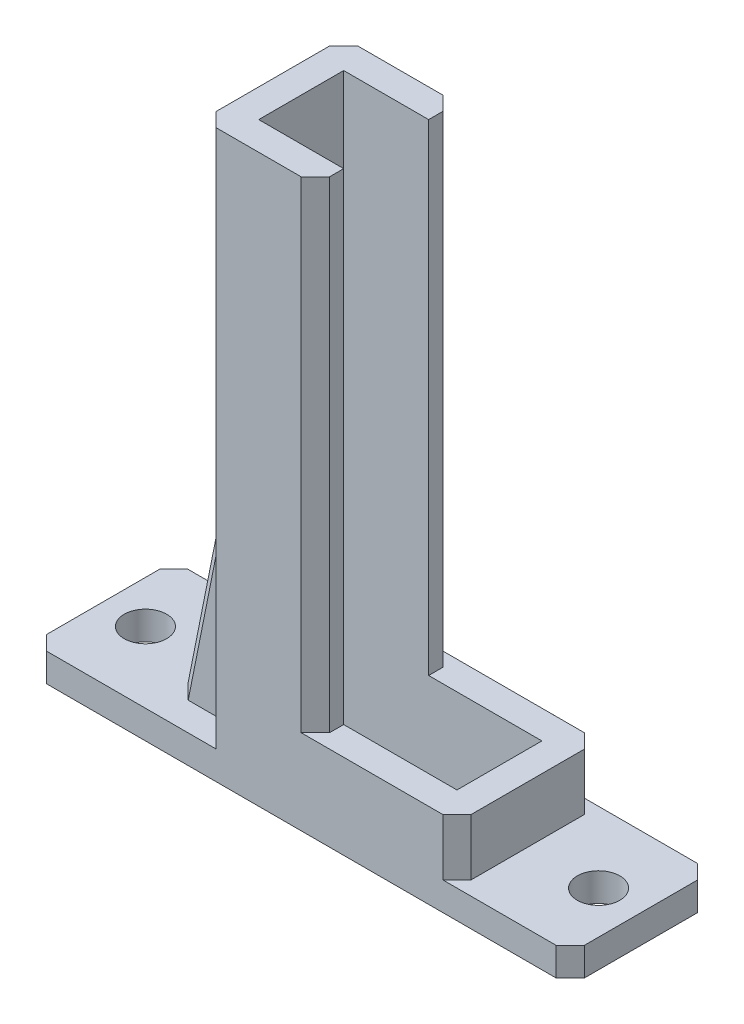
SolidWorks part; units mm, degrees
ref_plane "Front Plane" through (0, 0, 0) normal (0, 0, 1) x (1, 0, 0)
ref_plane "Top Plane" through (0, 0, 0) normal (0, 1, 0) x (1, 0, 0)
ref_plane "Right Plane" through (0, 0, 0) normal (1, 0, 0) x (0, 0, -1)
sketch "Sketch1" plane through (0, 0, 0) normal (0, 1, 0) x (1, 0, 0)
  line L0 (2, 2) -> (2, 8)
  line L1 (0, 0) -> (18, 0)
  line L2 (0, 0) -> (0, 10)
  line L3 (0, 10) -> (18, 10)
  line L4 (18, 0) -> (18, 10)
  line L5 (2, 8) -> (16, 8)
  line L6 (16, 2) -> (16, 8)
  line L7 (2, 2) -> (16, 2)
  dimension "D1" = 10
  dimension "D2" = 18
  dimension "D4" = 14
  dimension "D3" = 2
extrude "Boss-Extrude1" add sketch "Sketch1" along normal blind 6
sketch "Sketch2" plane through (0, 6, 0) normal (0, 1, 0) x (1, 0, 0)
  line L0 (0, 10) -> (0, 0)
  line L1 (0, 0) -> (8, 0)
  line L2 (0, 0) -> (18, 0) construction
  line L3 (8, 0) -> (8, 2)
  line L4 (2, 2) -> (16, 2) construction
  line L5 (8, 2) -> (2, 2)
  line L6 (2, 2) -> (2, 8)
  line L7 (2, 8) -> (8, 8)
  line L8 (16, 8) -> (2, 8) construction
  line L9 (8, 8) -> (8, 10)
  line L10 (18, 10) -> (0, 10) construction
  line L11 (8, 10) -> (0, 10)
  dimension "D1" = 6
  dimension "D2" = 6
extrude "Boss-Extrude2" add sketch "Sketch2" along normal blind 34
sketch "Sketch3" plane through (0, 0, 0) normal (0, 1, 0) x (1, 0, 0)
  line L1 (0, 0) -> (-12, 0)
  line L2 (0, 0) -> (0, 10)
  line L3 (0, 10) -> (-12, 10)
  line L4 (-12, 0) -> (-12, 10)
  line L5 (18, 0) -> (26, 0)
  line L6 (18, 0) -> (18, 10)
  line L7 (18, 10) -> (26, 10)
  line L8 (26, 0) -> (26, 10)
  dimension "D1" = 10
  dimension "D2" = 10
  dimension "D3" = 8
  dimension "D4" = 12
extrude "Boss-Extrude3" add sketch "Sketch3" along normal blind 2
ref_plane "Plane1" through (0, 0, -5) normal (0, 0, 1) x (1, 0, 0)
sketch "Sketch4" plane through (0, 0, -5) normal (0, 0, 1) x (1, 0, 0)
  line L0 (0, 2) -> (-4, 2)
  line L1 (-12, 2) -> (0, 2) construction
  line L2 (-4, 2) -> (0, 22)
  line L3 (0, 40) -> (0, 2) construction
  line L4 (0, 22) -> (0, 2)
  dimension "D1" = 4
  dimension "D2" = 20
extrude "Boss-Extrude4" add sketch "Sketch4" along normal blind 3 and the other way blind 3
chamfer "Chamfer1" distance 1 angle 45 10 edges at (-12, 1, 0) (-12, 1, -10) (26, 1, -10) (26, 1, 0) (18, 4, -10) (18, 4, 0) (8, 23, -10) (8, 23, 0) (0, 21, -10) (0, 21, 0)
chamfer "Chamfer2" distance 1 angle 45 2 edges at (-2, 12, -2) (-2, 12, -8)
sketch "Sketch5" plane through (0, 2, 0) normal (0, 1, 0) x (1, 0, 0)
  line L0 (-12, 5) -> (26, 5) construction
  line L1 (-12, 9) -> (-12, 1) construction
  line L2 (26, 1) -> (26, 9) construction
  circle A0 centre (-9, 5) radius 1.5
  circle A1 centre (23, 5) radius 1.5
  dimension "D1" = 3
  dimension "D2" = 3
  dimension "D3" = 3
  dimension "D4" = 3
extrude "Cut-Extrude1" cut sketch "Sketch5" against normal through all
